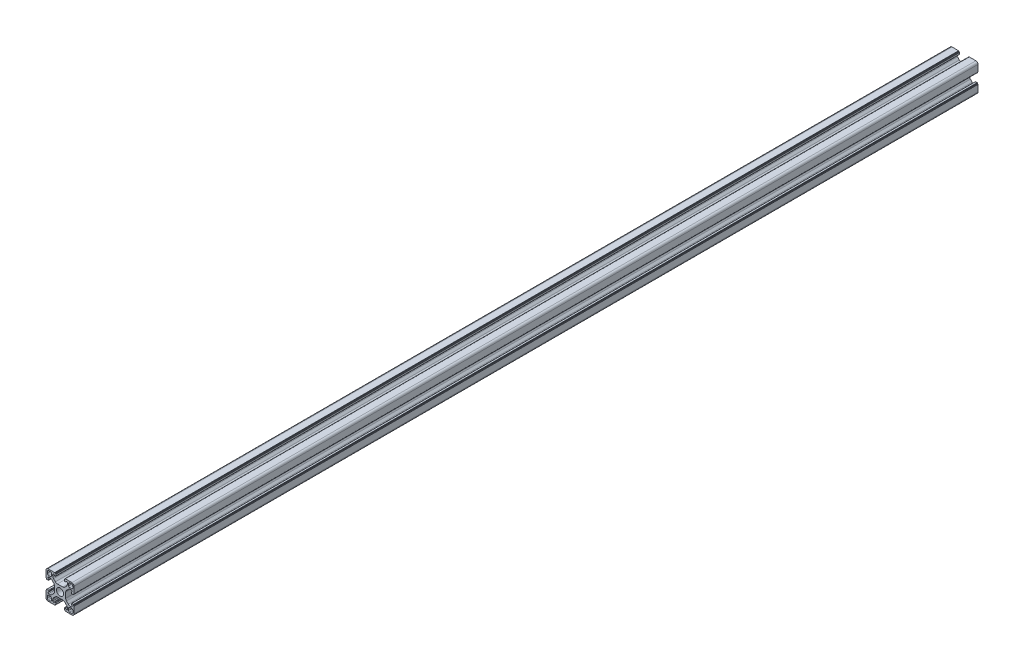
SolidWorks part; units mm, degrees
ref_plane "Спереди" through (0, 0, 0) normal (0, 0, 1) x (1, 0, 0)
ref_plane "Сверху" through (0, 0, 0) normal (0, 1, 0) x (1, 0, 0)
ref_plane "Справа" through (0, 0, 0) normal (1, 0, 0) x (0, 0, -1)
sketch "Эскиз1" plane through (0, 0, 0) normal (0, 0, 1) x (1, 0, 0)
  line L0 (-9.367, 48.5619) -> (-12.367, 45.5619) construction
  line L1 (-18.467, 43.4619) -> (-16.5682, 43.4619)
  line L2 (-18.467, 39.4619) -> (-8.467, 49.4619) construction
  line L3 (-10.867, 47.0619) -> (-12.367, 48.5619) construction
  line L4 (-15.154, 44.0477) -> (-13.8528, 45.3489)
  line L5 (-11.567, 45.5619) -> (-10.167, 45.5619)
  line L6 (-12.367, 46.3619) -> (-12.367, 47.7619)
  line L7 (-10.167, 48.5619) -> (-11.567, 48.5619)
  line L8 (-13.267, 47.6619) -> (-13.267, 46.7631)
  line L9 (-14.7038, 47.5351) -> (-14.2234, 48.0154)
  line L10 (-15.267, 49.0109) -> (-14.767, 49.0109)
  line L11 (-14.8805, 47.4619) -> (-15.167, 47.4619)
  line L12 (-13.8699, 48.1619) -> (-13.767, 48.1619)
  line L13 (-14.767, 49.3119) -> (-14.767, 49.0109)
  line L14 (-15.417, 48.8609) -> (-15.417, 47.7119)
  line L15 (-9.967, 49.4619) -> (-14.617, 49.4619)
  line L16 (-9.367, 47.7619) -> (-9.367, 46.3619)
  line L17 (-8.467, 47.9619) -> (-8.467, 43.3119)
  line L18 (-9.0679, 42.5119) -> (-10.217, 42.5119)
  line L19 (-8.617, 43.1619) -> (-8.9179, 43.1619)
  line L20 (-9.767, 44.059) -> (-9.767, 44.1619)
  line L21 (-10.467, 43.0483) -> (-10.467, 42.7619)
  line L22 (-8.9179, 42.6619) -> (-8.9179, 43.1619)
  line L23 (-10.3938, 43.2251) -> (-9.9134, 43.7054)
  line L24 (-10.267, 44.6619) -> (-11.1658, 44.6619)
  line L25 (-13.8812, 42.7749) -> (-12.58, 44.0761)
  line L26 (-14.467, 39.4619) -> (-14.467, 41.3607)
  line L27 (-14.467, 39.4619) -> (-14.467, 37.5631)
  line L28 (-13.8812, 36.1489) -> (-12.58, 34.8477)
  line L29 (-12.367, 32.5619) -> (-12.367, 31.1619)
  line L30 (-11.567, 33.3619) -> (-10.167, 33.3619)
  line L31 (-9.367, 31.1619) -> (-9.367, 32.5619)
  line L32 (-10.267, 34.2619) -> (-11.1658, 34.2619)
  line L33 (-10.3938, 35.6987) -> (-9.9134, 35.2183)
  line L34 (-8.9179, 36.2619) -> (-8.9179, 35.7619)
  line L35 (-10.467, 35.8754) -> (-10.467, 36.1619)
  line L36 (-9.767, 34.8648) -> (-9.767, 34.7619)
  line L37 (-8.617, 35.7619) -> (-8.9179, 35.7619)
  line L38 (-9.0679, 36.4119) -> (-10.217, 36.4119)
  line L39 (-8.467, 30.9619) -> (-8.467, 35.6119)
  line L40 (-10.167, 30.3619) -> (-11.567, 30.3619)
  line L41 (-9.967, 29.4619) -> (-14.617, 29.4619)
  line L42 (-15.417, 30.0628) -> (-15.417, 31.2119)
  line L43 (-14.767, 29.6119) -> (-14.767, 29.9128)
  line L44 (-13.8699, 30.7619) -> (-13.767, 30.7619)
  line L45 (-14.8805, 31.4619) -> (-15.167, 31.4619)
  line L46 (-15.267, 29.9128) -> (-14.767, 29.9128)
  line L47 (-14.7038, 31.3887) -> (-14.2234, 30.9083)
  line L48 (-13.267, 31.2619) -> (-13.267, 32.1607)
  line L49 (-15.154, 34.8761) -> (-13.8528, 33.5749)
  line L50 (-18.467, 35.4619) -> (-16.5682, 35.4619)
  line L51 (-9.367, 30.3619) -> (-12.367, 33.3619) construction
  line L52 (-18.467, 39.4619) -> (-8.467, 29.4619) construction
  line L53 (-10.867, 31.8619) -> (-9.367, 33.3619) construction
  line L54 (-18.467, 35.4619) -> (-20.3658, 35.4619)
  line L55 (-21.78, 34.8761) -> (-23.0812, 33.5749)
  line L56 (-25.367, 33.3619) -> (-26.767, 33.3619)
  line L57 (-24.567, 32.5619) -> (-24.567, 31.1619)
  line L58 (-26.767, 30.3619) -> (-25.367, 30.3619)
  line L59 (-23.667, 31.2619) -> (-23.667, 32.1607)
  line L60 (-22.2302, 31.3887) -> (-22.7105, 30.9083)
  line L61 (-21.667, 29.9128) -> (-22.167, 29.9128)
  line L62 (-22.0534, 31.4619) -> (-21.767, 31.4619)
  line L63 (-23.0641, 30.7619) -> (-23.167, 30.7619)
  line L64 (-22.167, 29.6119) -> (-22.167, 29.9128)
  line L65 (-21.517, 30.0628) -> (-21.517, 31.2119)
  line L66 (-26.967, 29.4619) -> (-22.317, 29.4619)
  line L67 (-27.567, 31.1619) -> (-27.567, 32.5619)
  line L68 (-28.467, 30.9619) -> (-28.467, 35.6119)
  line L69 (-27.8661, 36.4119) -> (-26.717, 36.4119)
  line L70 (-28.317, 35.7619) -> (-28.0161, 35.7619)
  line L71 (-27.167, 34.8648) -> (-27.167, 34.7619)
  line L72 (-26.467, 35.8754) -> (-26.467, 36.1619)
  line L73 (-28.0161, 36.2619) -> (-28.0161, 35.7619)
  line L74 (-26.5402, 35.6987) -> (-27.0205, 35.2183)
  line L75 (-26.667, 34.2619) -> (-25.7682, 34.2619)
  line L76 (-23.0528, 36.1489) -> (-24.354, 34.8477)
  line L77 (-22.467, 39.4619) -> (-22.467, 37.5631)
  line L78 (-27.567, 30.3619) -> (-24.567, 33.3619) construction
  line L79 (-18.467, 39.4619) -> (-28.467, 29.4619) construction
  line L80 (-26.067, 31.8619) -> (-24.567, 30.3619) construction
  line L81 (-22.467, 39.4619) -> (-22.467, 41.3607)
  line L82 (-23.0528, 42.7749) -> (-24.354, 44.0761)
  line L83 (-24.567, 46.3619) -> (-24.567, 47.7619)
  line L84 (-25.367, 45.5619) -> (-26.767, 45.5619)
  line L85 (-27.567, 47.7619) -> (-27.567, 46.3619)
  line L86 (-26.667, 44.6619) -> (-25.7682, 44.6619)
  line L87 (-26.5402, 43.2251) -> (-27.0205, 43.7054)
  line L88 (-28.0161, 42.6619) -> (-28.0161, 43.1619)
  line L89 (-26.467, 43.0483) -> (-26.467, 42.7619)
  line L90 (-27.167, 44.059) -> (-27.167, 44.1619)
  line L91 (-28.317, 43.1619) -> (-28.0161, 43.1619)
  line L92 (-27.8661, 42.5119) -> (-26.717, 42.5119)
  line L93 (-28.467, 47.9619) -> (-28.467, 43.3119)
  line L94 (-26.767, 48.5619) -> (-25.367, 48.5619)
  line L95 (-26.967, 49.4619) -> (-22.317, 49.4619)
  line L96 (-21.517, 48.8609) -> (-21.517, 47.7119)
  line L97 (-22.167, 49.3119) -> (-22.167, 49.0109)
  line L98 (-23.0641, 48.1619) -> (-23.167, 48.1619)
  line L99 (-22.0534, 47.4619) -> (-21.767, 47.4619)
  line L100 (-21.667, 49.0109) -> (-22.167, 49.0109)
  line L101 (-22.2302, 47.5351) -> (-22.7105, 48.0154)
  line L102 (-23.667, 47.6619) -> (-23.667, 46.7631)
  line L103 (-21.78, 44.0477) -> (-23.0812, 45.3489)
  line L104 (-18.467, 43.4619) -> (-20.3658, 43.4619)
  line L105 (-30.231, 39.4619) -> (-6.9626, 39.4619) construction
  line L106 (-27.567, 48.5619) -> (-24.567, 45.5619) construction
  line L107 (-18.467, 27.3755) -> (-18.467, 50.1808) construction
  line L108 (-18.467, 39.4619) -> (-28.467, 49.4619) construction
  line L109 (-26.067, 47.0619) -> (-27.567, 45.5619) construction
  arc A0 (-9.367, 47.7619) -> (-10.167, 48.5619) centre (-10.167, 47.7619) ccw
  arc A1 (-11.567, 48.5619) -> (-12.367, 47.7619) centre (-11.567, 47.7619) ccw
  arc A2 (-11.567, 45.5619) -> (-12.367, 46.3619) centre (-11.567, 46.3619) cw
  arc A3 (-9.967, 49.4619) -> (-8.467, 47.9619) centre (-9.967, 47.9619) cw
  arc A4 (-15.267, 49.0109) -> (-15.417, 48.8609) centre (-15.267, 48.8609) ccw
  arc A5 (-14.617, 49.4619) -> (-14.767, 49.3119) centre (-14.617, 49.3119) ccw
  arc A6 (-14.8805, 47.4619) -> (-14.7038, 47.5351) centre (-14.8805, 47.7119) ccw
  arc A7 (-15.167, 47.4619) -> (-15.417, 47.7119) centre (-15.167, 47.7119) cw
  arc A8 (-14.2234, 48.0154) -> (-13.8699, 48.1619) centre (-13.8699, 47.6619) cw
  arc A9 (-13.767, 48.1619) -> (-13.267, 47.6619) centre (-13.767, 47.6619) cw
  arc A10 (-15.967, 39.4619) -> (-18.467, 41.9619) centre (-18.467, 39.4619) ccw
  arc A11 (-16.5682, 43.4619) -> (-15.154, 44.0477) centre (-16.5682, 45.4619) ccw
  arc A12 (-13.267, 46.7631) -> (-13.8528, 45.3489) centre (-15.267, 46.7631) cw
  arc A13 (-9.367, 46.3619) -> (-10.167, 45.5619) centre (-10.167, 46.3619) cw
  arc A14 (-9.767, 44.1619) -> (-10.267, 44.6619) centre (-10.267, 44.1619) ccw
  arc A15 (-9.9134, 43.7054) -> (-9.767, 44.059) centre (-10.267, 44.059) ccw
  arc A16 (-10.467, 42.7619) -> (-10.217, 42.5119) centre (-10.217, 42.7619) ccw
  arc A17 (-10.467, 43.0483) -> (-10.3938, 43.2251) centre (-10.217, 43.0483) cw
  arc A18 (-8.467, 43.3119) -> (-8.617, 43.1619) centre (-8.617, 43.3119) cw
  arc A19 (-8.9179, 42.6619) -> (-9.0679, 42.5119) centre (-9.0679, 42.6619) cw
  arc A20 (-11.1658, 44.6619) -> (-12.58, 44.0761) centre (-11.1658, 42.6619) ccw
  arc A21 (-14.467, 41.3607) -> (-13.8812, 42.7749) centre (-12.467, 41.3607) cw
  arc A22 (-10.167, 30.3619) -> (-9.367, 31.1619) centre (-10.167, 31.1619) ccw
  arc A23 (-9.367, 32.5619) -> (-10.167, 33.3619) centre (-10.167, 32.5619) ccw
  arc A24 (-12.367, 32.5619) -> (-11.567, 33.3619) centre (-11.567, 32.5619) cw
  arc A25 (-8.467, 30.9619) -> (-9.967, 29.4619) centre (-9.967, 30.9619) cw
  arc A26 (-8.9179, 36.2619) -> (-9.0679, 36.4119) centre (-9.0679, 36.2619) ccw
  arc A27 (-8.467, 35.6119) -> (-8.617, 35.7619) centre (-8.617, 35.6119) ccw
  arc A28 (-10.467, 35.8754) -> (-10.3938, 35.6987) centre (-10.217, 35.8754) ccw
  arc A29 (-10.467, 36.1619) -> (-10.217, 36.4119) centre (-10.217, 36.1619) cw
  arc A30 (-9.9134, 35.2183) -> (-9.767, 34.8648) centre (-10.267, 34.8648) cw
  arc A31 (-9.767, 34.7619) -> (-10.267, 34.2619) centre (-10.267, 34.7619) cw
  arc A32 (-18.467, 36.9619) -> (-15.967, 39.4619) centre (-18.467, 39.4619) ccw
  arc A33 (-14.467, 37.5631) -> (-13.8812, 36.1489) centre (-12.467, 37.5631) ccw
  arc A34 (-11.1658, 34.2619) -> (-12.58, 34.8477) centre (-11.1658, 36.2619) cw
  arc A35 (-11.567, 30.3619) -> (-12.367, 31.1619) centre (-11.567, 31.1619) cw
  arc A36 (-13.767, 30.7619) -> (-13.267, 31.2619) centre (-13.767, 31.2619) ccw
  arc A37 (-14.2234, 30.9083) -> (-13.8699, 30.7619) centre (-13.8699, 31.2619) ccw
  arc A38 (-15.167, 31.4619) -> (-15.417, 31.2119) centre (-15.167, 31.2119) ccw
  arc A39 (-14.8805, 31.4619) -> (-14.7038, 31.3887) centre (-14.8805, 31.2119) cw
  arc A40 (-14.617, 29.4619) -> (-14.767, 29.6119) centre (-14.617, 29.6119) cw
  arc A41 (-15.267, 29.9128) -> (-15.417, 30.0628) centre (-15.267, 30.0628) cw
  arc A42 (-13.267, 32.1607) -> (-13.8528, 33.5749) centre (-15.267, 32.1607) ccw
  arc A43 (-16.5682, 35.4619) -> (-15.154, 34.8761) centre (-16.5682, 33.4619) cw
  arc A44 (-27.567, 31.1619) -> (-26.767, 30.3619) centre (-26.767, 31.1619) ccw
  arc A45 (-25.367, 30.3619) -> (-24.567, 31.1619) centre (-25.367, 31.1619) ccw
  arc A46 (-25.367, 33.3619) -> (-24.567, 32.5619) centre (-25.367, 32.5619) cw
  arc A47 (-26.967, 29.4619) -> (-28.467, 30.9619) centre (-26.967, 30.9619) cw
  arc A48 (-21.667, 29.9128) -> (-21.517, 30.0628) centre (-21.667, 30.0628) ccw
  arc A49 (-22.317, 29.4619) -> (-22.167, 29.6119) centre (-22.317, 29.6119) ccw
  arc A50 (-22.0534, 31.4619) -> (-22.2302, 31.3887) centre (-22.0534, 31.2119) ccw
  arc A51 (-21.767, 31.4619) -> (-21.517, 31.2119) centre (-21.767, 31.2119) cw
  arc A52 (-22.7105, 30.9083) -> (-23.0641, 30.7619) centre (-23.0641, 31.2619) cw
  arc A53 (-23.167, 30.7619) -> (-23.667, 31.2619) centre (-23.167, 31.2619) cw
  arc A54 (-20.967, 39.4619) -> (-18.467, 36.9619) centre (-18.467, 39.4619) ccw
  arc A55 (-20.3658, 35.4619) -> (-21.78, 34.8761) centre (-20.3658, 33.4619) ccw
  arc A56 (-23.667, 32.1607) -> (-23.0812, 33.5749) centre (-21.667, 32.1607) cw
  arc A57 (-27.567, 32.5619) -> (-26.767, 33.3619) centre (-26.767, 32.5619) cw
  arc A58 (-27.167, 34.7619) -> (-26.667, 34.2619) centre (-26.667, 34.7619) ccw
  arc A59 (-27.0205, 35.2183) -> (-27.167, 34.8648) centre (-26.667, 34.8648) ccw
  arc A60 (-26.467, 36.1619) -> (-26.717, 36.4119) centre (-26.717, 36.1619) ccw
  arc A61 (-26.467, 35.8754) -> (-26.5402, 35.6987) centre (-26.717, 35.8754) cw
  arc A62 (-28.467, 35.6119) -> (-28.317, 35.7619) centre (-28.317, 35.6119) cw
  arc A63 (-28.0161, 36.2619) -> (-27.8661, 36.4119) centre (-27.8661, 36.2619) cw
  arc A64 (-25.7682, 34.2619) -> (-24.354, 34.8477) centre (-25.7682, 36.2619) ccw
  arc A65 (-22.467, 37.5631) -> (-23.0528, 36.1489) centre (-24.467, 37.5631) cw
  arc A66 (-26.767, 48.5619) -> (-27.567, 47.7619) centre (-26.767, 47.7619) ccw
  arc A67 (-27.567, 46.3619) -> (-26.767, 45.5619) centre (-26.767, 46.3619) ccw
  arc A68 (-24.567, 46.3619) -> (-25.367, 45.5619) centre (-25.367, 46.3619) cw
  arc A69 (-28.467, 47.9619) -> (-26.967, 49.4619) centre (-26.967, 47.9619) cw
  arc A70 (-28.0161, 42.6619) -> (-27.8661, 42.5119) centre (-27.8661, 42.6619) ccw
  arc A71 (-28.467, 43.3119) -> (-28.317, 43.1619) centre (-28.317, 43.3119) ccw
  arc A72 (-26.467, 43.0483) -> (-26.5402, 43.2251) centre (-26.717, 43.0483) ccw
  arc A73 (-26.467, 42.7619) -> (-26.717, 42.5119) centre (-26.717, 42.7619) cw
  arc A74 (-27.0205, 43.7054) -> (-27.167, 44.059) centre (-26.667, 44.059) cw
  arc A75 (-27.167, 44.1619) -> (-26.667, 44.6619) centre (-26.667, 44.1619) cw
  arc A76 (-18.467, 41.9619) -> (-20.967, 39.4619) centre (-18.467, 39.4619) ccw
  arc A77 (-22.467, 41.3607) -> (-23.0528, 42.7749) centre (-24.467, 41.3607) ccw
  arc A78 (-25.7682, 44.6619) -> (-24.354, 44.0761) centre (-25.7682, 42.6619) cw
  arc A79 (-25.367, 48.5619) -> (-24.567, 47.7619) centre (-25.367, 47.7619) cw
  arc A80 (-23.167, 48.1619) -> (-23.667, 47.6619) centre (-23.167, 47.6619) ccw
  arc A81 (-22.7105, 48.0154) -> (-23.0641, 48.1619) centre (-23.0641, 47.6619) ccw
  arc A82 (-21.767, 47.4619) -> (-21.517, 47.7119) centre (-21.767, 47.7119) ccw
  arc A83 (-22.0534, 47.4619) -> (-22.2302, 47.5351) centre (-22.0534, 47.7119) cw
  arc A84 (-22.317, 49.4619) -> (-22.167, 49.3119) centre (-22.317, 49.3119) cw
  arc A85 (-21.667, 49.0109) -> (-21.517, 48.8609) centre (-21.667, 48.8609) cw
  arc A86 (-23.667, 46.7631) -> (-23.0812, 45.3489) centre (-21.667, 46.7631) ccw
  arc A87 (-20.3658, 43.4619) -> (-21.78, 44.0477) centre (-20.3658, 45.4619) cw
  point P0 (-18.467, 39.4619)
  point P9 (-18.467, 39.4619)
  point P40 (-9.767, 43.1619)
  point P93 (-14.767, 30.7619)
  point P144 (-14.767, 48.1619)
  point P152 (-9.767, 35.7619)
  point P153 (-18.467, 35.5376)
  point P154 (-18.467, 39.4619)
  point P189 (-27.167, 35.7619)
  point P228 (-22.167, 30.7619)
  point P229 (-22.3912, 39.4619)
  point P230 (-18.467, 39.4619)
  point P268 (-22.167, 48.1619)
  point P273 (-14.5427, 39.4619)
  point P306 (-27.167, 43.1619)
  point P307 (-18.467, 43.3861)
  point P309 (-18.467, 39.4619)
  dimension "D3" = 5
  dimension "D6" = 2
  dimension "D1" = 2
  dimension "D2" = 6
  dimension "D4" = 4
  dimension "D5" = 0.9
extrude "Бобышка-Вытянуть1" add sketch "Эскиз1" along normal blind 644
